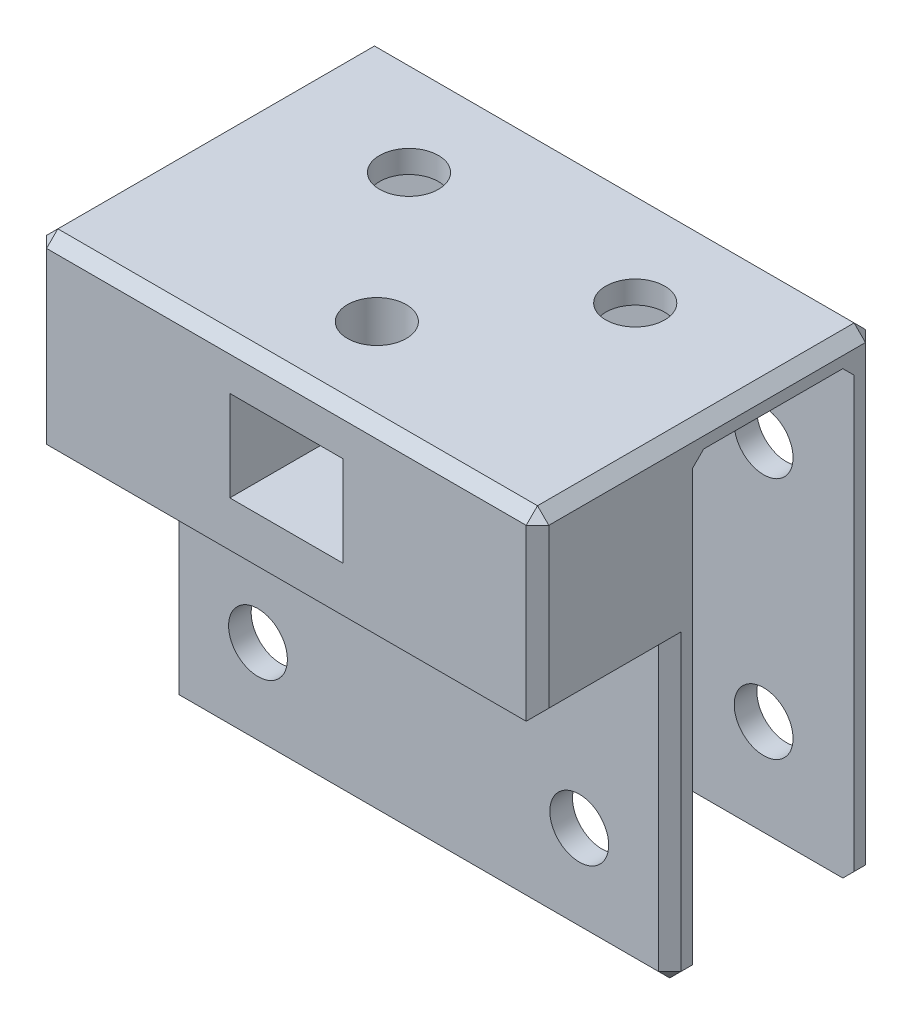
SolidWorks part; units mm, degrees
ref_plane "Front Plane" through (0, 0, 0) normal (0, 0, 1) x (1, 0, 0)
ref_plane "Top Plane" through (0, 0, 0) normal (0, 1, 0) x (1, 0, 0)
ref_plane "Right Plane" through (0, 0, 0) normal (1, 0, 0) x (0, 0, -1)
sketch "Sketch1" plane through (0, 0, 0) normal (0, 0, 1) x (1, 0, 0)
  line L0 (22.2, 40) -> (22.2, 0) construction
  line L1 (0, 0) -> (44.4, 0)
  line L2 (0, 0) -> (0, 40)
  line L3 (0, 40) -> (44.4, 40)
  line L4 (44.4, 0) -> (44.4, 40)
  line L5 (0, 0) -> (8, 0) construction
  line L6 (0, 0) -> (0, 8) construction
  line L10 (8, 29.9769) -> (8, 27.3769) construction
  line L11 (8, 19) -> (8, 8.4769) construction
  line L12 (8, 19) -> (10.573, 19) construction
  line L15 (10.573, 19) -> (10.573, 40) construction
  line L16 (8, 8.4769) -> (36.4, 8.4769) construction
  line L17 (36.4, 8.4769) -> (36.4, 29.9769) construction
  circle A0 centre (8, 8.4769) radius 2.6
  circle A1 centre (8, 29.9769) radius 2.6
  circle A2 centre (36.4, 29.9769) radius 2.6
  circle A3 centre (36.4, 8.4769) radius 2.6
  dimension "D5" = 5.2
  dimension "D6" = 5.2
  dimension "D7" = 5.2
  dimension "D8" = 5.2
  dimension "D1" = 44.4
  dimension "D2" = 40
  dimension "D3" = 21.5
  dimension "D4" = 21.5
  dimension "D9" = 21
  dimension "D10" = 8
  dimension "D11" = 8
extrude "Boss-Extrude1" add sketch "Sketch1" along normal blind 2
sketch "Sketch2" plane through (0, 40, 0) normal (0, 1, 0) x (1, 0, 0)
  line L0 (44.4, -2) -> (44.4, 0) construction
  line L1 (0, -2) -> (44.4, -2)
  line L2 (0, -2) -> (0, 16.3)
  line L3 (0, 16.3) -> (44.4, 16.3)
  line L4 (44.4, -2) -> (44.4, 16.3)
  dimension "D1" = 18.3
  dimension "D2" = 44.4
extrude "Boss-Extrude2" add sketch "Sketch2" along normal blind 2
pattern_linear "LPattern1" count 2 spacing 16.3 along (0, 0, -1) of "Boss-Extrude1"
sketch "Sketch3" plane through (0, 42, 0) normal (0, 1, 0) x (1, 0, 0)
  line L0 (22.2, 16.3) -> (22.2, -2) construction
  line L1 (44.4, 16.3) -> (0, 16.3) construction
  line L2 (0, -2) -> (44.4, -2) construction
  line L3 (22.2, 7.15) -> (12.2, 7.15) construction
  line L4 (22.2, 7.15) -> (32.2, 7.15) construction
  circle A0 centre (12.2, 7.15) radius 2.6
  circle A1 centre (32.2, 7.15) radius 2.6
  dimension "D3" = 5.2
  dimension "D4" = 5.2
  dimension "D1" = 10
  dimension "D2" = 10
extrude "Cut-Extrude1" cut sketch "Sketch3" against normal through all
sketch "Sketch5" plane through (0, 0, -16.3) normal (0, 0, -1) x (-1, 0, 0)
  line L1 (-22.2, 41) -> (-22.2, 34.93) construction
  dimension "D1" = 6.07
ref_plane "Plane1" through (22.2, 0, 0) normal (1, 0, 0) x (0, 0, -1)
sketch "Sketch6" plane through (22.2, 0, 0) normal (1, 0, 0) x (0, 0, -1)
  line L0 (16.3, 42) -> (-2, 42) construction
  line L1 (16.3, 41) -> (16.3, 34.93) construction
  line L3 (-2, 42) -> (-13.69, 42)
  line L4 (-13.69, 42) -> (-13.69, 26)
  line L5 (-13.69, 26) -> (-2, 26)
  line L6 (-2, 26) -> (-2, 42)
  dimension "D1" = 11.69
  dimension "D2" = 16
extrude "Boss-Extrude3" add sketch "Sketch6" along normal up to surface and the other way up to surface
fillet "Fillet4" radius 1 20 edges at (22.2, 40, -14.3) (22.2, 40, 0) (22.2, 42, -16.3) (0, 42, -1.305) (44.4, 42, -1.305) (44.4, 21, -16.3) (44.4, 34, 13.69) (44.4, 13, 2) (0, 21, -16.3) (0, 13, 2) (0, 34, 13.69) (44.4, 0, 1) (0, 0, 1) (44.4, 0, -15.3) (0, 0, -15.3) (22.2, 0, -16.3) (22.2, 0, 2) (22.2, 42, 13.69) (44.4, 26, 7.845) (0, 26, 7.845) profile chamfer
sketch "Sketch11" plane through (0, 42, 0) normal (0, 1, 0) x (1, 0, 0)
  line L0 (22.2, -13.69) -> (22.2, -5.69) construction
  line L5 (43.4, -13.69) -> (1, -13.69) construction
  circle A0 centre (22.2, -5.69) radius 2.6
  dimension "D2" = 5.2
  dimension "D1" = 8
sketch "Sketch12" plane through (0, 26, 0) normal (0, -1, 0) x (1, 0, 0)
  line L1 (3, 2) -> (13, 2)
  line L2 (3, 2) -> (3, 10.3844)
  line L3 (3, 10.3844) -> (13, 10.3844)
  line L4 (41.4, 2) -> (41.4, 10.3844)
  line L6 (1, 13.69) -> (1, 2) construction
  line L7 (31.4, 10.3844) -> (31.4, 2)
  line L10 (43.4, 2) -> (43.4, 13.69) construction
  line L11 (3, 10.3844) -> (13, 10.3844)
  line L12 (3, 10.3844) -> (3, 2)
  line L13 (3, 2) -> (13, 2)
  line L14 (13, 10.3844) -> (13, 2)
  line L15 (31.4, 10.3844) -> (41.4, 10.3844)
  line L16 (31.4, 2) -> (41.4, 2)
  line L17 (43.4, 2) -> (1, 2) construction
  dimension "D1" = 2
  dimension "D2" = 2
  dimension "D4" = 10
  dimension "D5" = 10
extrude "Cut-Extrude7" cut sketch "Sketch12" against normal offset from surface (11 mm away) 5
extrude "Cut-Extrude8" cut sketch "Sketch11" against normal blind 10
sketch "Sketch13" plane through (0, 0, 13.69) normal (0, 0, 1) x (1, 0, 0)
  line L0 (22.2, 42) -> (22.2, 34) construction
  line L1 (1, 42) -> (43.4, 42) construction
  line L2 (27.2, 38) -> (17.2, 38)
  line L3 (27.2, 38) -> (27.2, 30)
  line L4 (17.2, 38) -> (17.2, 30)
  line L5 (27.2, 30) -> (17.2, 30)
  line L6 (17.2, 34) -> (27.2, 34) construction
  line L7 (22.2, 38) -> (22.2, 30) construction
  dimension "D1" = 8
  dimension "D2" = 8
  dimension "D3" = 10
extrude "Cut-Extrude9" cut sketch "Sketch13" against normal up to surface (11.69 mm away) up to face at (22.2, 25.5, 2)
